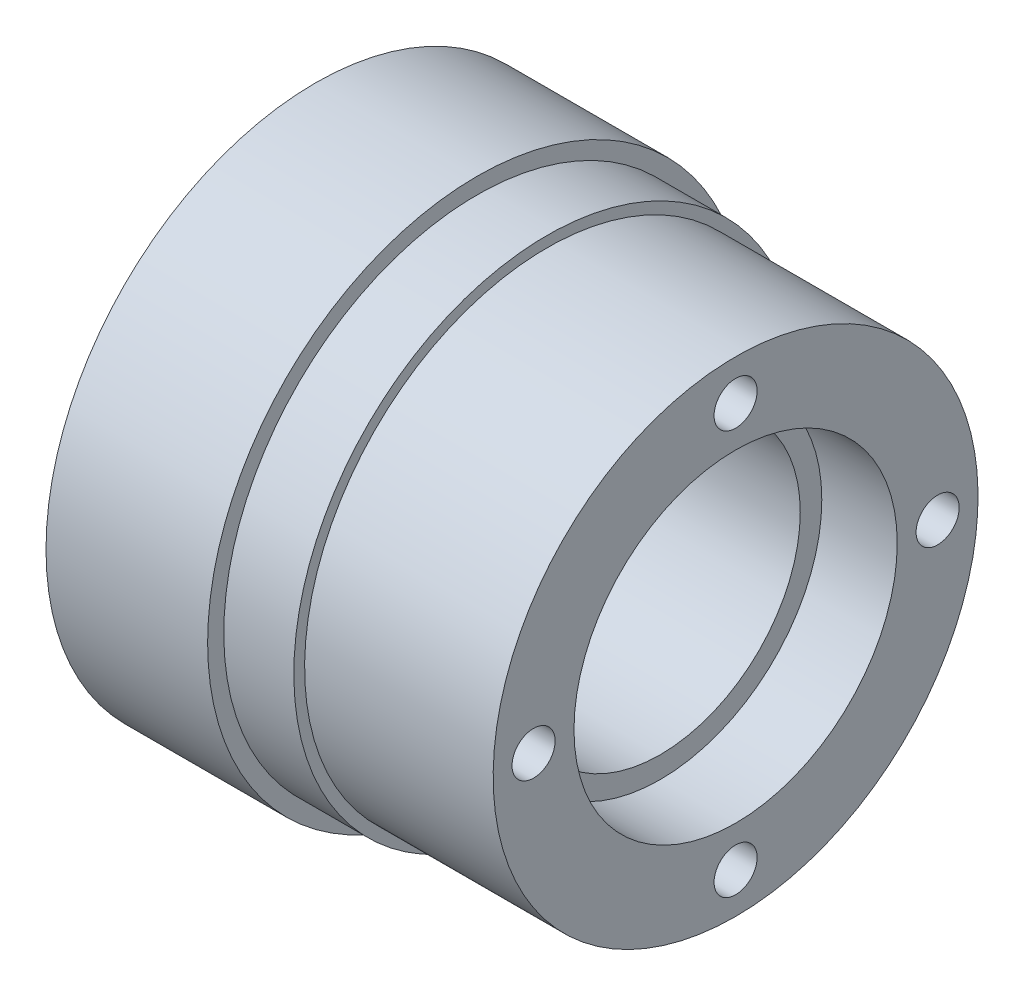
SolidWorks part; units mm, degrees
material "2024-T4"
ref_plane "Front Plane" through (0, 0, 0) normal (0, 0, 1) x (1, 0, 0)
ref_plane "Top Plane" through (0, 0, 0) normal (0, 1, 0) x (1, 0, 0)
ref_plane "Right Plane" through (0, 0, 0) normal (1, 0, 0) x (0, 0, -1)
sketch "Sketch1" plane through (0, 0, 0) normal (0, 0, 1) x (1, 0, 0)
  line L0 (-19.5, 0) -> (19.5, 0) construction
  line L1 (-19.5, 13.5) -> (-15.3, 13.5)
  line L2 (-15.3, 13.5) -> (-15.3, 13)
  line L3 (-15.3, 13) -> (12.5, 13)
  line L4 (12.5, 13) -> (12.5, 15)
  line L5 (12.5, 15) -> (19.5, 15)
  line L6 (19.5, 15) -> (19.5, 22.5)
  line L7 (19.5, 22.5) -> (2, 22.5)
  line L8 (2, 22.5) -> (2, 23.5)
  line L9 (2, 23.5) -> (-4.5, 23.5)
  line L10 (-4.5, 23.5) -> (-4.5, 25)
  line L11 (-4.5, 25) -> (-19.5, 25)
  line L12 (-19.5, 25) -> (-19.5, 13.5)
  point P4 (0, 0)
  point P21 (2, 23)
  dimension "D1" = 39
  dimension "D2" = 7
  dimension "D3" = 26
  dimension "D4" = 27
  dimension "D5" = 30
  dimension "D6" = 4.2
  dimension "D7" = 50
  dimension "D8" = 45
  dimension "D9" = 47
  dimension "D10" = 15
  dimension "D11" = 17.5
revolve "Revolve1" add sketch "Sketch1" angle 360 about L0
sketch "Sketch2" plane through (19.5, 0, 0) normal (1, 0, 0) x (0, 0, -1)
  line L0 (0, 22.5) -> (0, 15) construction
  circle A0 centre (0, 18.75) radius 2
  circle A1 centre (0, 0) radius 22.5 construction
  circle A2 centre (0, 0) radius 22.5 construction
  circle A3 centre (0, 0) radius 15 construction
  circle A4 centre (18.75, 0) radius 2
  circle A5 centre (0, -18.75) radius 2
  circle A6 centre (-18.75, 0) radius 2
  point P21 (0, 0)
  dimension "D1" = 4
  dimension "D2" = 18.75
  dimension "D3" = 18.75
extrude "Cut-Extrude1" cut sketch "Sketch2" against normal blind 10
sketch "Sketch3" plane through (-19.5, 0, 0) normal (-1, 0, 0) x (0, 0, 1)
  line L0 (0, 13.5) -> (0, 25) construction
  circle A0 centre (0, 0) radius 13.5 construction
  circle A1 centre (0, 0) radius 13.5 construction
  circle A2 centre (0, 0) radius 25 construction
  circle A3 centre (0, 19.25) radius 2
  circle A4 centre (19.25, 0) radius 2
  circle A5 centre (0, -19.25) radius 2
  circle A6 centre (-19.25, 0) radius 2
  point P19 (0, 0)
  dimension "D1" = 4
  dimension "D2" = 19.25
  dimension "D3" = 19.25
extrude "Cut-Extrude2" cut sketch "Sketch3" against normal blind 10
equation "\"mini-flipper-shaft-diameter\"= 26mm"
equation "\"mini-shaft-ring-groove-diam\"= 7.8mm"
equation "\"mini-shaft-ring-groove-width\"= 1mm"
equation "\"dtCoverPlate-DistFrom-GearCent\"= 73mm"
equation "\"wormGearShaft-L\"= \"dtCoverPlate-DistFrom-GearCent\" - 27.75 + 3.75"
equation "\"wormGearShaft-Dsmall\"= 6mm"
equation "\"wormGearShaft-Dworm\"= 12mm"
equation "\"wormL-D\" = 12mm"
equation "\"wormR-D\" = 15mm"
equation "\"wormGearL-D\" = 40mm"
equation "\"wormGearR-D\" = 50mm"
equation "\"D7@Sketch1\"=\"wormGearR-D\""
